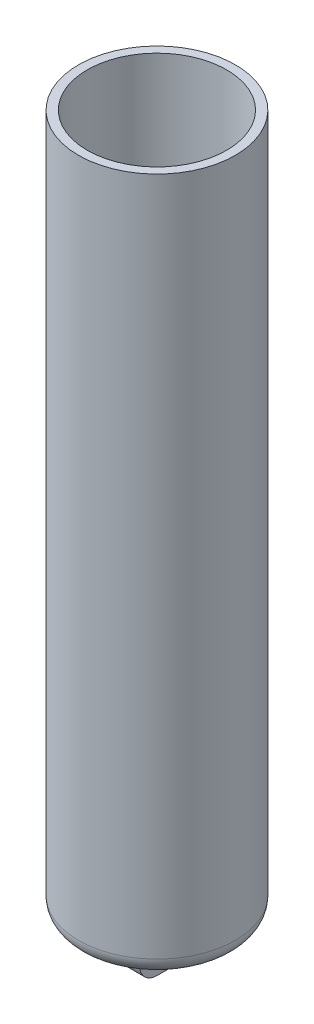
SolidWorks part; units mm, degrees
ref_plane "前视基准面" through (0, 0, 0) normal (0, 0, 1) x (1, 0, 0)
ref_plane "上视基准面" through (0, 0, 0) normal (0, 1, 0) x (1, 0, 0)
ref_plane "右视基准面" through (0, 0, 0) normal (1, 0, 0) x (0, 0, -1)
sketch "草图1" plane through (0, 0, 0) normal (0, 1, 0) x (1, 0, 0)
  circle A0 centre (0, 0) radius 9
  dimension "D1" = 18
extrude "凸台-拉伸1" add sketch "草图1" along normal blind 80
sketch "草图2" plane through (0, 80, 0) normal (0, 1, 0) x (1, 0, 0)
  circle A0 centre (0, 0) radius 8
  circle A1 centre (0, 0) radius 9 construction
  dimension "D1" = 16
extrude "切除-拉伸1" cut sketch "草图2" against normal blind 77
sketch "草图3" plane through (0, 0, 0) normal (0, -1, 0) x (-1, 0, 0)
  line L1 (-1, 3) -> (1, 3)
  line L2 (-1, 3) -> (-1, -3)
  line L3 (-1, -3) -> (1, -3)
  line L4 (1, 3) -> (1, -3)
  line L5 (-1, 3) -> (1, -3) construction
  line L6 (-1, -3) -> (1, 3) construction
  point P0 (0, 0)
  dimension "D1" = 2
  dimension "D2" = 6
extrude "凸台-拉伸2" add sketch "草图3" along normal blind 5
sketch "草图4" plane through (1, 0, 0) normal (1, 0, 0) x (0, 0, -1)
  circle A0 centre (0, -2.5156) radius 1.25
  dimension "D1" = 2.5
extrude "切除-拉伸2" cut sketch "草图4" against normal blind 5
fillet "圆角1" radius 2 1 edges at (0, -5, -3)
fillet "圆角2" radius 2 1 edges at (0, -5, 3)
fillet "圆角3" radius 2 1 edges at (0, 0, 9)
equation "\"、\"=5"
